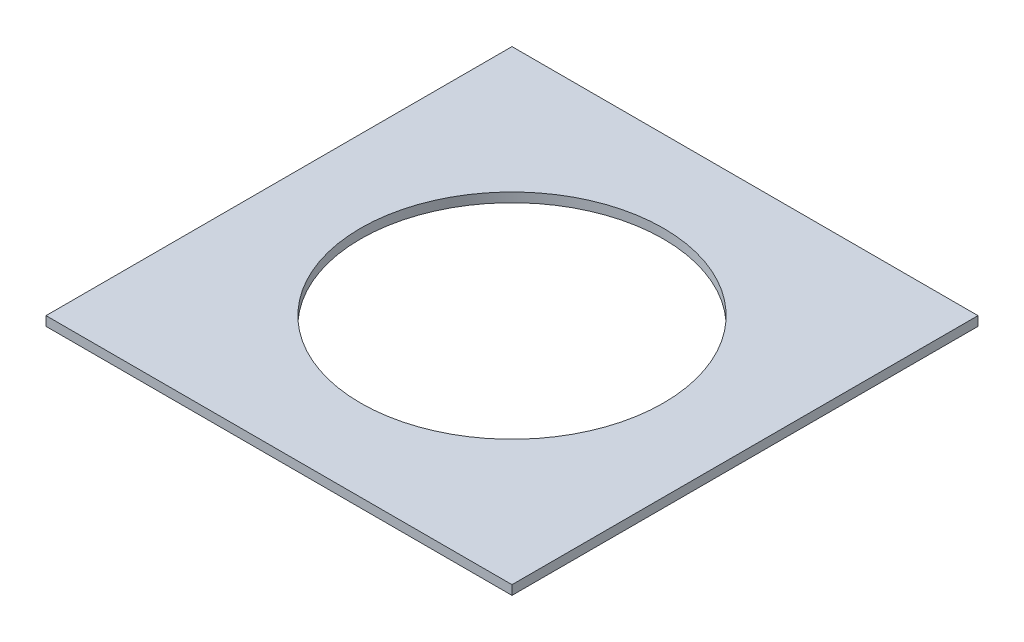
SolidWorks part; units mm, degrees
material "AISI 316 Stainless Steel Sheet (SS)"
ref_plane "Front Plane" through (0, 0, 0) normal (0, 0, 1) x (1, 0, 0)
ref_plane "Top Plane" through (0, 0, 0) normal (0, 1, 0) x (1, 0, 0)
ref_plane "Right Plane" through (0, 0, 0) normal (1, 0, 0) x (0, 0, -1)
sketch "Sketch1" plane through (0, 0, 0) normal (0, 1, 0) x (1, 0, 0)
  line L1 (-250, 250) -> (250, 250)
  line L2 (-250, 250) -> (-250, -250)
  line L3 (-250, -250) -> (250, -250)
  line L4 (250, 250) -> (250, -250)
  line L5 (-250, 250) -> (250, -250) construction
  line L6 (-250, -250) -> (250, 250) construction
  circle A0 centre (0, 0) radius 162.5
  point P0 (0, 0)
  dimension "D3" = 325
  dimension "D1" = 500
  dimension "D2" = 500
extrude "Boss-Extrude1" add sketch "Sketch1" along normal mid plane 10
